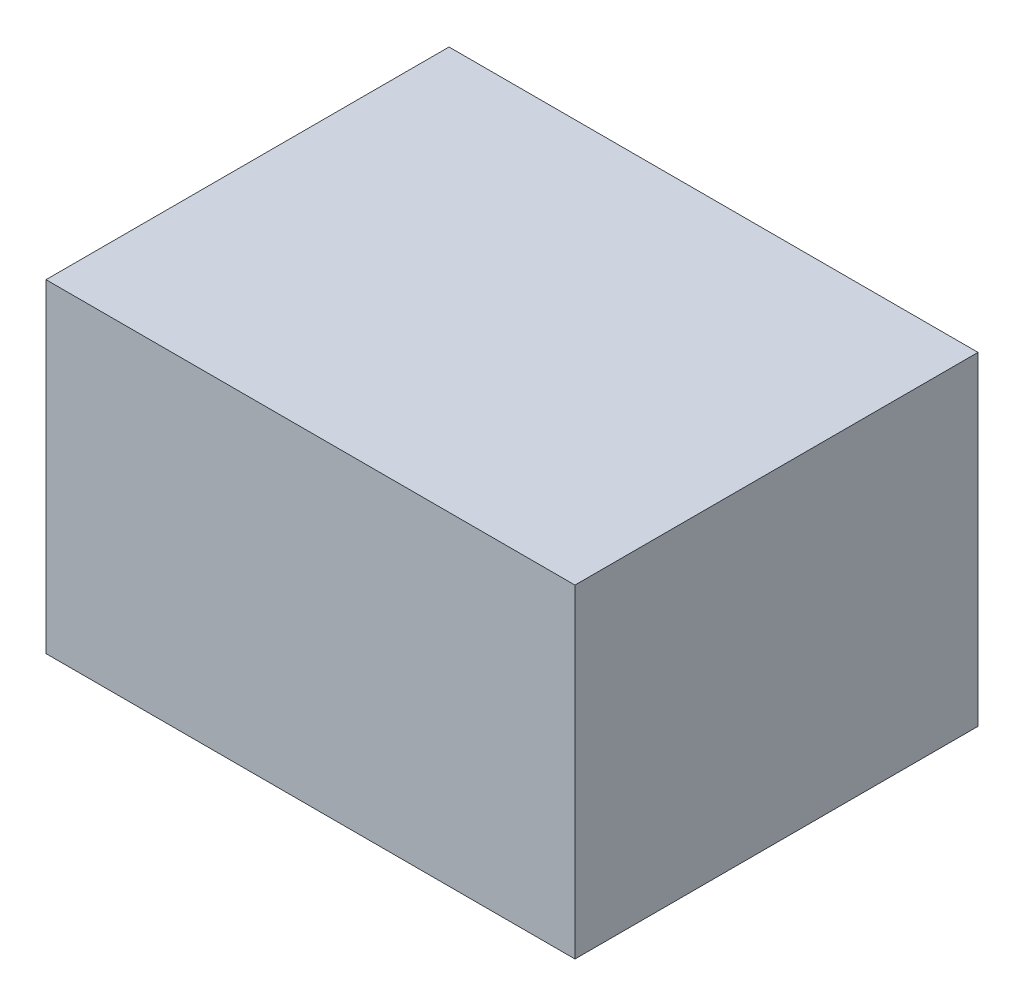
SolidWorks part; units mm, degrees
material "Air"
ref_plane "Front Plane" through (0, 0, 0) normal (0, 0, 1) x (1, 0, 0)
ref_plane "Top Plane" through (0, 0, 0) normal (0, 1, 0) x (1, 0, 0)
ref_plane "Right Plane" through (0, 0, 0) normal (1, 0, 0) x (0, 0, -1)
sketch "Sketch1" plane through (0, 0, 0) normal (0, 1, 0) x (1, 0, 0)
  line L1 (-186.69, -142.24) -> (186.69, -142.24)
  line L2 (-186.69, -142.24) -> (-186.69, 142.24)
  line L3 (-186.69, 142.24) -> (186.69, 142.24)
  line L4 (186.69, -142.24) -> (186.69, 142.24)
  line L5 (-186.69, -142.24) -> (186.69, 142.24) construction
  line L6 (-186.69, 142.24) -> (186.69, -142.24) construction
  point P0 (0, 0)
  dimension "D1" = 373.38
  dimension "D2" = 284.48
extrude "Boss-Extrude1" add sketch "Sketch1" along normal mid plane 228.6
